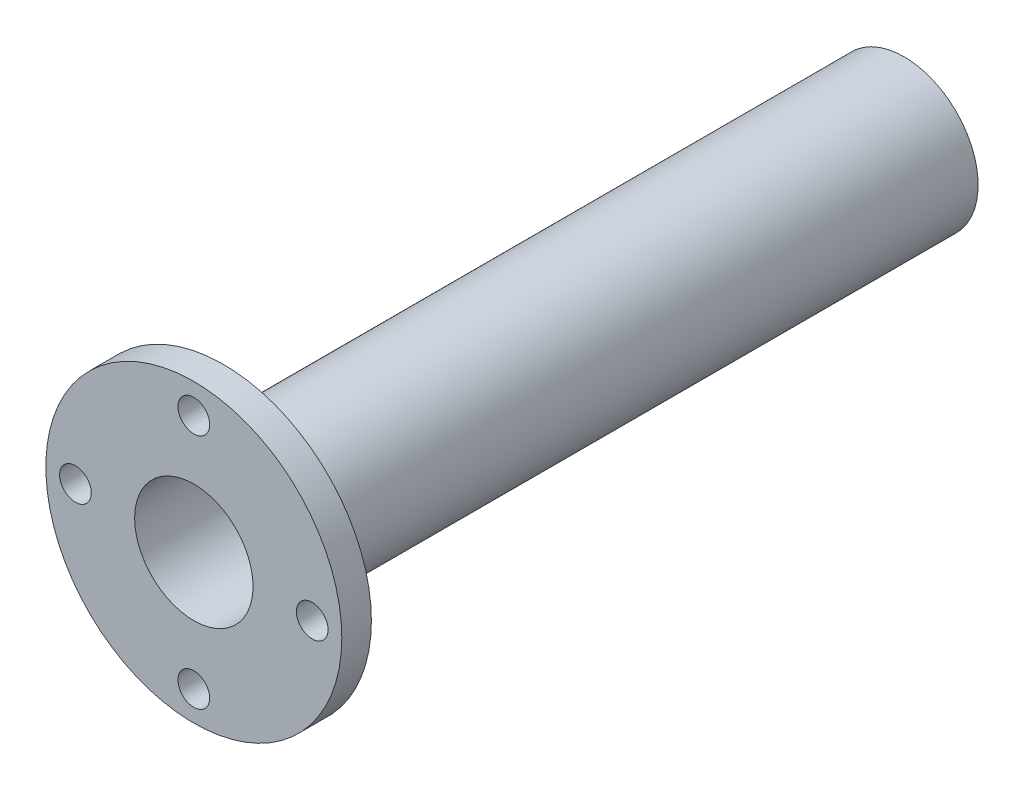
SolidWorks part; units mm, degrees
material "Tin Bearing Bronze"
ref_plane "Front Plane" through (0, 0, 0) normal (0, 0, 1) x (1, 0, 0)
ref_plane "Top Plane" through (0, 0, 0) normal (0, 1, 0) x (1, 0, 0)
ref_plane "Right Plane" through (0, 0, 0) normal (1, 0, 0) x (0, 0, -1)
sketch "Sketch1" plane through (0, 0, 0) normal (0, 0, 1) x (1, 0, 0)
  circle A0 centre (0, 0) radius 6.35
  circle A1 centre (0, 0) radius 7.9375
  dimension "D1" = 15.875
  dimension "D2" = 12.7
extrude "Boss-Extrude1" add sketch "Sketch1" along normal blind 76.2
sketch "Sketch2" plane through (0, 0, 76.2) normal (0, 0, 1) x (1, 0, 0)
  circle A0 centre (0, 0) radius 15.875
  circle A1 centre (0, 0) radius 6.35 construction
  circle A2 centre (0, 0) radius 6.35
  dimension "D1" = 31.75
extrude "Boss-Extrude2" add sketch "Sketch2" against normal blind 3.175
hole_wizard "M3 Clearance Hole1" positions "Sketch4" profile "Sketch5" hole size "M3" standard "ANSI Metric"
sketch "Sketch4" plane through (0, 0, 76.2) normal (0, 0, 1) x (1, 0, 0)
  point P0 (0, 12.7)
  point P2 (0, -12.7)
  point P4 (12.7, 0)
  point P6 (-12.7, 0)
  dimension "D1" = 12.7
  dimension "D2" = 12.7
  dimension "D3" = 12.7
  dimension "D4" = 12.7
sketch "Sketch5" plane through (0, 12.7, 76.2) normal (1, 0, 0) x (0, -1, 0)
  line L0 (0, 0) -> (0, 5.0215)
  line L1 (0, 5.0215) -> (1.7, 4)
  line L2 (1.7, 4) -> (1.7, 0)
  line L5 (1.7, 0) -> (0, 0)
  line L10 (0, 5.0215) -> (-1.7, 4) construction
  line L11 (0, -6.35) -> (0, 107.95) construction
  dimension "Hole Dia." = 3.4
  dimension "Hole Depth" = 4
  dimension "Drill Angle" = 118
